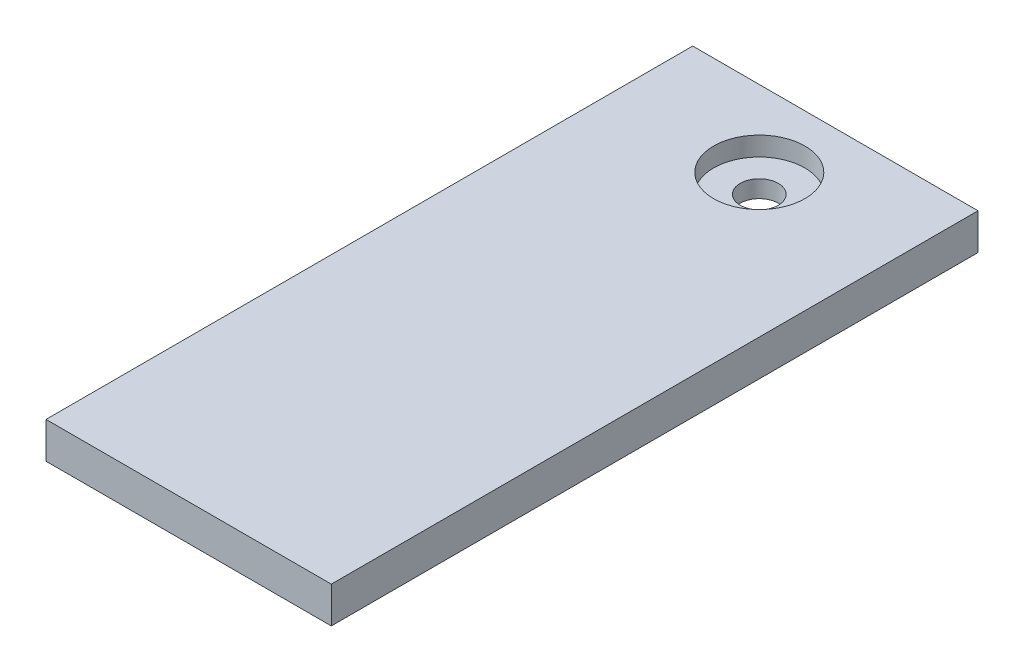
SolidWorks part; units mm, degrees
ref_plane "Alzado" through (0, 0, 0) normal (0, 0, 1) x (1, 0, 0)
ref_plane "Planta" through (0, 0, 0) normal (0, 1, 0) x (1, 0, 0)
ref_plane "Vista lateral" through (0, 0, 0) normal (1, 0, 0) x (0, 0, -1)
sketch "Croquis1" plane through (0, 0, 0) normal (0, 1, 0) x (1, 0, 0)
  line L1 (37.5, -85) -> (-37.5, -85)
  line L2 (37.5, -85) -> (37.5, 85)
  line L3 (37.5, 85) -> (-37.5, 85)
  line L4 (-37.5, -85) -> (-37.5, 85)
  line L5 (37.5, -85) -> (-37.5, 85) construction
  line L6 (37.5, 85) -> (-37.5, -85) construction
  circle A0 centre (0, 65) radius 5
  point P0 (0, 0)
  point P8 (0, 0)
  point P9 (0, 0)
  dimension "D2" = 10
  dimension "D1" = 20
  dimension "D3" = 75
  dimension "D4" = 170
extrude "Saliente-Extruir1" add sketch "Croquis1" along normal blind 9.525
sketch "Croquis2" plane through (0, 9.525, 0) normal (0, 1, 0) x (1, 0, 0)
  circle A0 centre (0, 65) radius 12
  dimension "D1" = 24
extrude "Cortar-Extruir1" cut sketch "Croquis2" against normal blind 5
